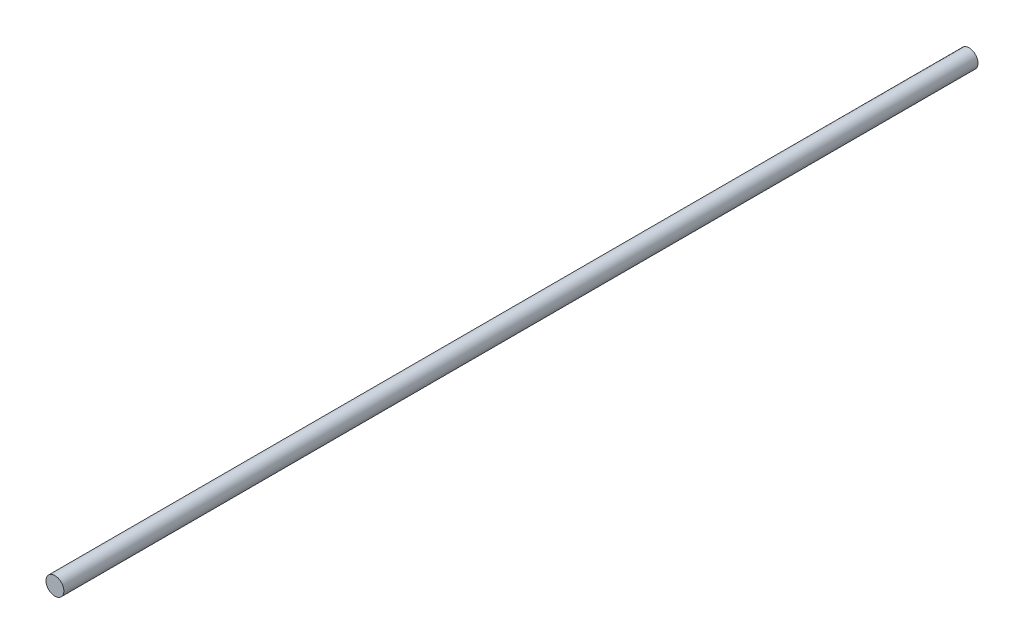
SolidWorks part; units mm, degrees
material "Chrome Stainless Steel"
ref_plane "Front Plane" through (0, 0, 0) normal (0, 0, 1) x (1, 0, 0)
ref_plane "Top Plane" through (0, 0, 0) normal (0, 1, 0) x (1, 0, 0)
ref_plane "Right Plane" through (0, 0, 0) normal (1, 0, 0) x (0, 0, -1)
sketch "Sketch1" plane through (0, 0, 0) normal (0, 0, 1) x (1, 0, 0)
  circle A0 centre (0, 0) radius 9.779
extrude "Boss-Extrude1" add sketch "Sketch1" along normal blind 1000
